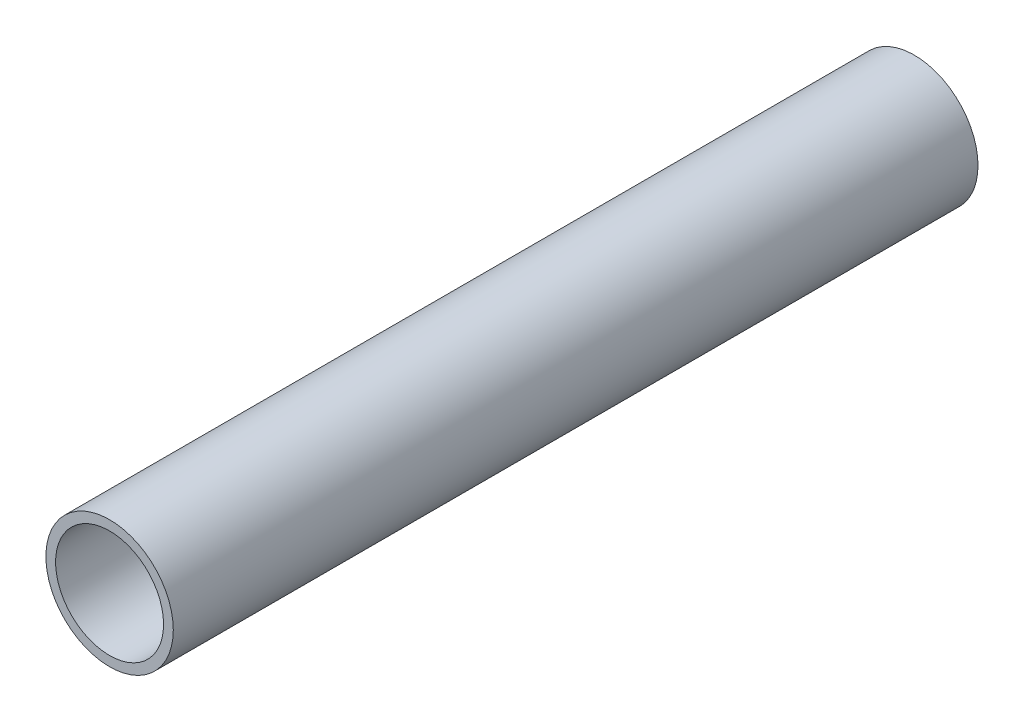
SolidWorks part; units mm, degrees
ref_plane "Front Plane" through (0, 0, 0) normal (0, 0, 1) x (1, 0, 0)
ref_plane "Top Plane" through (0, 0, 0) normal (0, 1, 0) x (1, 0, 0)
ref_plane "Right Plane" through (0, 0, 0) normal (1, 0, 0) x (0, 0, -1)
sketch "Sketch1" plane through (0, 0, 0) normal (1, 0, 0) x (0, 0, -1)
  line L0 (-152.4, 0) -> (152.4, 0) construction
  line L1 (152.4, 24.13) -> (152.4, -24.13) construction
  line L2 (-152.4, 24.13) -> (-152.4, -24.13) construction
  circle A0 centre (-152.4, 0) radius 20.447 construction
  point P0 (0, 0)
  point P9 (-152.4, 20.447)
  point P10 (-55.88, 0)
  point P11 (-152.4, -20.447)
  point P12 (55.88, 0)
  point P16 (-152.4, -24.13)
  dimension "Length" = 304.8
  dimension "OD" = 48.26
  dimension "Pipe Size" = 48.26
  dimension "Wall Thickness" = 3.683
  dimension "ID" = 40.894
  dimension "D1" = 96.52
  dimension "D2" = 96.52
sketch "Sketch3" plane through (0, 0, 0) normal (0, 0, 1) x (1, 0, 0)
  circle A0 centre (0, 0) radius 24.13
  circle A1 centre (0, 0) radius 20.447
  point P4 (-24.13, 0)
  point P6 (24.13, 0)
  point P8 (0, 24.13)
  point P9 (0, -24.13)
  point P10 (0, 20.447)
  point P11 (-20.447, 0)
  point P12 (20.447, 0)
extrude "Boss-Extrude1" add sketch "Sketch3" against normal up to vertex (152.4 mm away) and the other way up to vertex (152.4 mm away) up to point (0, 24.13, -152.4) other way up to point (0, 24.13, 152.4)
equation "\"D1@Sketch1\"=\"OD@Sketch1\"*2"
equation "\"D2@Sketch1\"=\"D1@Sketch1\""
